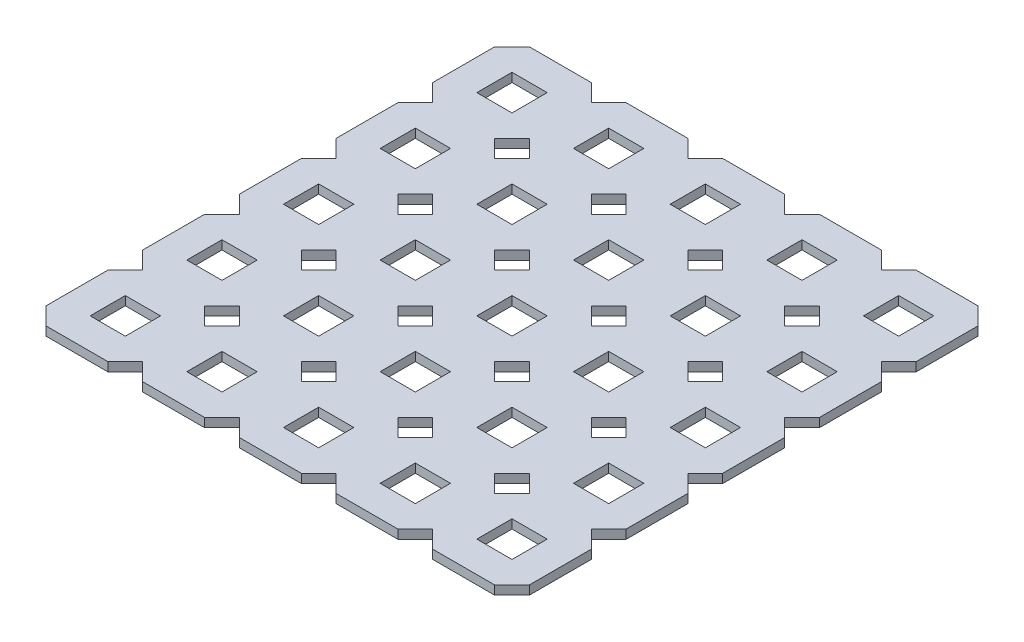
SolidWorks part; units mm, degrees
ref_plane "Front Plane" through (0, 0, 0) normal (0, 0, 1) x (1, 0, 0)
ref_plane "Top Plane" through (0, 0, 0) normal (0, 1, 0) x (1, 0, 0)
ref_plane "Right Plane" through (0, 0, 0) normal (1, 0, 0) x (0, 0, -1)
ref_plane "Plane1" through (0, 1.1684, 0) normal (0, 1, 0) x (1, 0, 0)
sketch "Sketch1" plane through (0, 1.1684, 0) normal (0, 1, 0) x (1, 0, 0)
  line L0 (14.981, 127) -> (12.7, 124.719)
  line L1 (12.7, 124.719) -> (10.419, 127)
  line L2 (10.419, 127) -> (2.281, 127)
  line L3 (2.281, 127) -> (0, 124.719)
  line L4 (0, 124.719) -> (0, 116.581)
  line L5 (0, 116.581) -> (2.281, 114.3)
  line L6 (2.281, 114.3) -> (0, 112.019)
  line L7 (0, 112.019) -> (0, 103.881)
  line L8 (0, 103.881) -> (2.281, 101.6)
  line L9 (2.281, 101.6) -> (0, 99.319)
  line L10 (0, 99.319) -> (0, 91.181)
  line L11 (0, 91.181) -> (2.281, 88.9)
  line L12 (2.281, 88.9) -> (0, 86.619)
  line L13 (0, 86.619) -> (0, 78.481)
  line L14 (0, 78.481) -> (2.281, 76.2)
  line L15 (2.281, 76.2) -> (0, 73.919)
  line L16 (0, 73.919) -> (0, 65.781)
  line L17 (0, 65.781) -> (2.281, 63.5)
  line L18 (2.281, 63.5) -> (10.419, 63.5)
  line L19 (14.981, 63.5) -> (23.119, 63.5)
  line L20 (27.681, 63.5) -> (35.819, 63.5)
  line L21 (40.381, 63.5) -> (48.519, 63.5)
  line L22 (53.081, 63.5) -> (61.219, 63.5)
  line L61 (61.219, 63.5) -> (63.5, 65.781)
  line L62 (63.5, 65.781) -> (63.5, 73.919)
  line L63 (63.5, 73.919) -> (61.219, 76.2)
  line L64 (61.219, 76.2) -> (63.5, 78.481)
  line L65 (63.5, 78.481) -> (63.5, 86.619)
  line L66 (63.5, 86.619) -> (61.219, 88.9)
  line L67 (61.219, 88.9) -> (63.5, 91.181)
  line L68 (63.5, 91.181) -> (63.5, 99.319)
  line L69 (63.5, 99.319) -> (61.219, 101.6)
  line L70 (61.219, 101.6) -> (63.5, 103.881)
  line L71 (63.5, 103.881) -> (63.5, 112.019)
  line L72 (63.5, 112.019) -> (61.219, 114.3)
  line L73 (61.219, 114.3) -> (63.5, 116.581)
  line L74 (63.5, 116.581) -> (63.5, 124.719)
  line L75 (63.5, 124.719) -> (61.219, 127)
  line L76 (61.219, 127) -> (53.081, 127)
  line L77 (53.081, 127) -> (50.8, 124.719)
  line L78 (50.8, 124.719) -> (48.519, 127)
  line L79 (48.519, 127) -> (40.381, 127)
  line L80 (40.381, 127) -> (38.1, 124.719)
  line L81 (38.1, 124.719) -> (35.819, 127)
  line L82 (35.819, 127) -> (27.681, 127)
  line L83 (27.681, 127) -> (25.4, 124.719)
  line L84 (25.4, 124.719) -> (23.119, 127)
  line L85 (23.119, 127) -> (14.981, 127)
  line L86 (12.7, 112.019) -> (10.419, 114.3)
  line L87 (10.419, 114.3) -> (12.7, 116.581)
  line L88 (12.7, 116.581) -> (14.981, 114.3)
  line L89 (14.981, 114.3) -> (12.7, 112.019)
  line L90 (12.7, 86.619) -> (10.419, 88.9)
  line L91 (10.419, 88.9) -> (12.7, 91.181)
  line L92 (12.7, 91.181) -> (14.981, 88.9)
  line L93 (14.981, 88.9) -> (12.7, 86.619)
  line L95 (10.419, 63.5) -> (12.7, 65.781)
  line L96 (12.7, 65.781) -> (14.981, 63.5)
  line L106 (25.4, 112.019) -> (23.119, 114.3)
  line L107 (23.119, 114.3) -> (25.4, 116.581)
  line L108 (25.4, 116.581) -> (27.681, 114.3)
  line L109 (27.681, 114.3) -> (25.4, 112.019)
  line L110 (25.4, 86.619) -> (23.119, 88.9)
  line L111 (23.119, 88.9) -> (25.4, 91.181)
  line L112 (25.4, 91.181) -> (27.681, 88.9)
  line L113 (27.681, 88.9) -> (25.4, 86.619)
  line L115 (23.119, 63.5) -> (25.4, 65.781)
  line L116 (25.4, 65.781) -> (27.681, 63.5)
  line L126 (38.1, 112.019) -> (35.819, 114.3)
  line L127 (35.819, 114.3) -> (38.1, 116.581)
  line L128 (38.1, 116.581) -> (40.381, 114.3)
  line L129 (40.381, 114.3) -> (38.1, 112.019)
  line L130 (38.1, 86.619) -> (35.819, 88.9)
  line L131 (35.819, 88.9) -> (38.1, 91.181)
  line L132 (38.1, 91.181) -> (40.381, 88.9)
  line L133 (40.381, 88.9) -> (38.1, 86.619)
  line L135 (35.819, 63.5) -> (38.1, 65.781)
  line L136 (38.1, 65.781) -> (40.381, 63.5)
  line L146 (50.8, 112.019) -> (48.519, 114.3)
  line L147 (48.519, 114.3) -> (50.8, 116.581)
  line L148 (50.8, 116.581) -> (53.081, 114.3)
  line L149 (53.081, 114.3) -> (50.8, 112.019)
  line L150 (50.8, 86.619) -> (48.519, 88.9)
  line L151 (48.519, 88.9) -> (50.8, 91.181)
  line L152 (50.8, 91.181) -> (53.081, 88.9)
  line L153 (53.081, 88.9) -> (50.8, 86.619)
  line L155 (48.519, 63.5) -> (50.8, 65.781)
  line L156 (50.8, 65.781) -> (53.081, 63.5)
  line L166 (8.6614, 122.9614) -> (8.6614, 118.3386)
  line L167 (8.6614, 118.3386) -> (4.0386, 118.3386)
  line L168 (4.0386, 118.3386) -> (4.0386, 122.9614)
  line L169 (4.0386, 122.9614) -> (8.6614, 122.9614)
  line L170 (21.3614, 122.9614) -> (21.3614, 118.3386)
  line L171 (21.3614, 118.3386) -> (16.7386, 118.3386)
  line L172 (16.7386, 118.3386) -> (16.7386, 122.9614)
  line L173 (16.7386, 122.9614) -> (21.3614, 122.9614)
  line L174 (34.0614, 122.9614) -> (34.0614, 118.3386)
  line L175 (34.0614, 118.3386) -> (29.4386, 118.3386)
  line L176 (29.4386, 118.3386) -> (29.4386, 122.9614)
  line L177 (29.4386, 122.9614) -> (34.0614, 122.9614)
  line L178 (46.7614, 122.9614) -> (46.7614, 118.3386)
  line L179 (46.7614, 118.3386) -> (42.1386, 118.3386)
  line L180 (42.1386, 118.3386) -> (42.1386, 122.9614)
  line L181 (42.1386, 122.9614) -> (46.7614, 122.9614)
  line L182 (59.4614, 122.9614) -> (59.4614, 118.3386)
  line L183 (59.4614, 118.3386) -> (54.8386, 118.3386)
  line L184 (54.8386, 118.3386) -> (54.8386, 122.9614)
  line L185 (54.8386, 122.9614) -> (59.4614, 122.9614)
  line L186 (8.6614, 110.2614) -> (8.6614, 105.6386)
  line L187 (8.6614, 105.6386) -> (4.0386, 105.6386)
  line L188 (4.0386, 105.6386) -> (4.0386, 110.2614)
  line L189 (4.0386, 110.2614) -> (8.6614, 110.2614)
  line L190 (59.4614, 110.2614) -> (59.4614, 105.6386)
  line L191 (59.4614, 105.6386) -> (54.8386, 105.6386)
  line L192 (54.8386, 105.6386) -> (54.8386, 110.2614)
  line L193 (54.8386, 110.2614) -> (59.4614, 110.2614)
  line L194 (8.6614, 97.5614) -> (8.6614, 92.9386)
  line L195 (8.6614, 92.9386) -> (4.0386, 92.9386)
  line L196 (4.0386, 92.9386) -> (4.0386, 97.5614)
  line L197 (4.0386, 97.5614) -> (8.6614, 97.5614)
  line L198 (59.4614, 97.5614) -> (59.4614, 92.9386)
  line L199 (59.4614, 92.9386) -> (54.8386, 92.9386)
  line L200 (54.8386, 92.9386) -> (54.8386, 97.5614)
  line L201 (54.8386, 97.5614) -> (59.4614, 97.5614)
  line L202 (8.6614, 84.8614) -> (8.6614, 80.2386)
  line L203 (8.6614, 80.2386) -> (4.0386, 80.2386)
  line L204 (4.0386, 80.2386) -> (4.0386, 84.8614)
  line L205 (4.0386, 84.8614) -> (8.6614, 84.8614)
  line L206 (59.4614, 84.8614) -> (59.4614, 80.2386)
  line L207 (59.4614, 80.2386) -> (54.8386, 80.2386)
  line L208 (54.8386, 80.2386) -> (54.8386, 84.8614)
  line L209 (54.8386, 84.8614) -> (59.4614, 84.8614)
  line L210 (8.6614, 72.1614) -> (8.6614, 67.5386)
  line L211 (8.6614, 67.5386) -> (4.0386, 67.5386)
  line L212 (4.0386, 67.5386) -> (4.0386, 72.1614)
  line L213 (4.0386, 72.1614) -> (8.6614, 72.1614)
  line L214 (59.4614, 72.1614) -> (59.4614, 67.5386)
  line L215 (59.4614, 67.5386) -> (54.8386, 67.5386)
  line L216 (54.8386, 67.5386) -> (54.8386, 72.1614)
  line L217 (54.8386, 72.1614) -> (59.4614, 72.1614)
  line L262 (21.3614, 110.2614) -> (21.3614, 105.6386)
  line L263 (21.3614, 105.6386) -> (16.7386, 105.6386)
  line L264 (16.7386, 105.6386) -> (16.7386, 110.2614)
  line L265 (16.7386, 110.2614) -> (21.3614, 110.2614)
  line L266 (34.0614, 110.2614) -> (34.0614, 105.6386)
  line L267 (34.0614, 105.6386) -> (29.4386, 105.6386)
  line L268 (29.4386, 105.6386) -> (29.4386, 110.2614)
  line L269 (29.4386, 110.2614) -> (34.0614, 110.2614)
  line L270 (46.7614, 110.2614) -> (46.7614, 105.6386)
  line L271 (46.7614, 105.6386) -> (42.1386, 105.6386)
  line L272 (42.1386, 105.6386) -> (42.1386, 110.2614)
  line L273 (42.1386, 110.2614) -> (46.7614, 110.2614)
  line L274 (21.3614, 97.5614) -> (21.3614, 92.9386)
  line L275 (21.3614, 92.9386) -> (16.7386, 92.9386)
  line L276 (16.7386, 92.9386) -> (16.7386, 97.5614)
  line L277 (16.7386, 97.5614) -> (21.3614, 97.5614)
  line L278 (34.0614, 97.5614) -> (34.0614, 92.9386)
  line L279 (34.0614, 92.9386) -> (29.4386, 92.9386)
  line L280 (29.4386, 92.9386) -> (29.4386, 97.5614)
  line L281 (29.4386, 97.5614) -> (34.0614, 97.5614)
  line L282 (46.7614, 97.5614) -> (46.7614, 92.9386)
  line L283 (46.7614, 92.9386) -> (42.1386, 92.9386)
  line L284 (42.1386, 92.9386) -> (42.1386, 97.5614)
  line L285 (42.1386, 97.5614) -> (46.7614, 97.5614)
  line L286 (21.3614, 84.8614) -> (21.3614, 80.2386)
  line L287 (21.3614, 80.2386) -> (16.7386, 80.2386)
  line L288 (16.7386, 80.2386) -> (16.7386, 84.8614)
  line L289 (16.7386, 84.8614) -> (21.3614, 84.8614)
  line L290 (34.0614, 84.8614) -> (34.0614, 80.2386)
  line L291 (34.0614, 80.2386) -> (29.4386, 80.2386)
  line L292 (29.4386, 80.2386) -> (29.4386, 84.8614)
  line L293 (29.4386, 84.8614) -> (34.0614, 84.8614)
  line L294 (46.7614, 84.8614) -> (46.7614, 80.2386)
  line L295 (46.7614, 80.2386) -> (42.1386, 80.2386)
  line L296 (42.1386, 80.2386) -> (42.1386, 84.8614)
  line L297 (42.1386, 84.8614) -> (46.7614, 84.8614)
  line L298 (21.3614, 72.1614) -> (21.3614, 67.5386)
  line L299 (21.3614, 67.5386) -> (16.7386, 67.5386)
  line L300 (16.7386, 67.5386) -> (16.7386, 72.1614)
  line L301 (16.7386, 72.1614) -> (21.3614, 72.1614)
  line L302 (34.0614, 72.1614) -> (34.0614, 67.5386)
  line L303 (34.0614, 67.5386) -> (29.4386, 67.5386)
  line L304 (29.4386, 67.5386) -> (29.4386, 72.1614)
  line L305 (29.4386, 72.1614) -> (34.0614, 72.1614)
  line L306 (46.7614, 72.1614) -> (46.7614, 67.5386)
  line L307 (46.7614, 67.5386) -> (42.1386, 67.5386)
  line L308 (42.1386, 67.5386) -> (42.1386, 72.1614)
  line L309 (42.1386, 72.1614) -> (46.7614, 72.1614)
  line L374 (50.8, 73.919) -> (48.519, 76.2)
  line L375 (48.519, 76.2) -> (50.8, 78.481)
  line L376 (50.8, 78.481) -> (53.081, 76.2)
  line L377 (53.081, 76.2) -> (50.8, 73.919)
  line L378 (50.8, 99.319) -> (48.519, 101.6)
  line L379 (48.519, 101.6) -> (50.8, 103.881)
  line L380 (50.8, 103.881) -> (53.081, 101.6)
  line L381 (53.081, 101.6) -> (50.8, 99.319)
  line L390 (38.1, 73.919) -> (35.819, 76.2)
  line L391 (35.819, 76.2) -> (38.1, 78.481)
  line L392 (38.1, 78.481) -> (40.381, 76.2)
  line L393 (40.381, 76.2) -> (38.1, 73.919)
  line L394 (38.1, 99.319) -> (35.819, 101.6)
  line L395 (35.819, 101.6) -> (38.1, 103.881)
  line L396 (38.1, 103.881) -> (40.381, 101.6)
  line L397 (40.381, 101.6) -> (38.1, 99.319)
  line L406 (25.4, 73.919) -> (23.119, 76.2)
  line L407 (23.119, 76.2) -> (25.4, 78.481)
  line L408 (25.4, 78.481) -> (27.681, 76.2)
  line L409 (27.681, 76.2) -> (25.4, 73.919)
  line L410 (25.4, 99.319) -> (23.119, 101.6)
  line L411 (23.119, 101.6) -> (25.4, 103.881)
  line L412 (25.4, 103.881) -> (27.681, 101.6)
  line L413 (27.681, 101.6) -> (25.4, 99.319)
  line L422 (12.7, 73.919) -> (10.419, 76.2)
  line L423 (10.419, 76.2) -> (12.7, 78.481)
  line L424 (12.7, 78.481) -> (14.981, 76.2)
  line L425 (14.981, 76.2) -> (12.7, 73.919)
  line L426 (12.7, 99.319) -> (10.419, 101.6)
  line L427 (10.419, 101.6) -> (12.7, 103.881)
  line L428 (12.7, 103.881) -> (14.981, 101.6)
  line L429 (14.981, 101.6) -> (12.7, 99.319)
extrude "Boss-Extrude1" add sketch "Sketch1" against normal blind 1.1684
